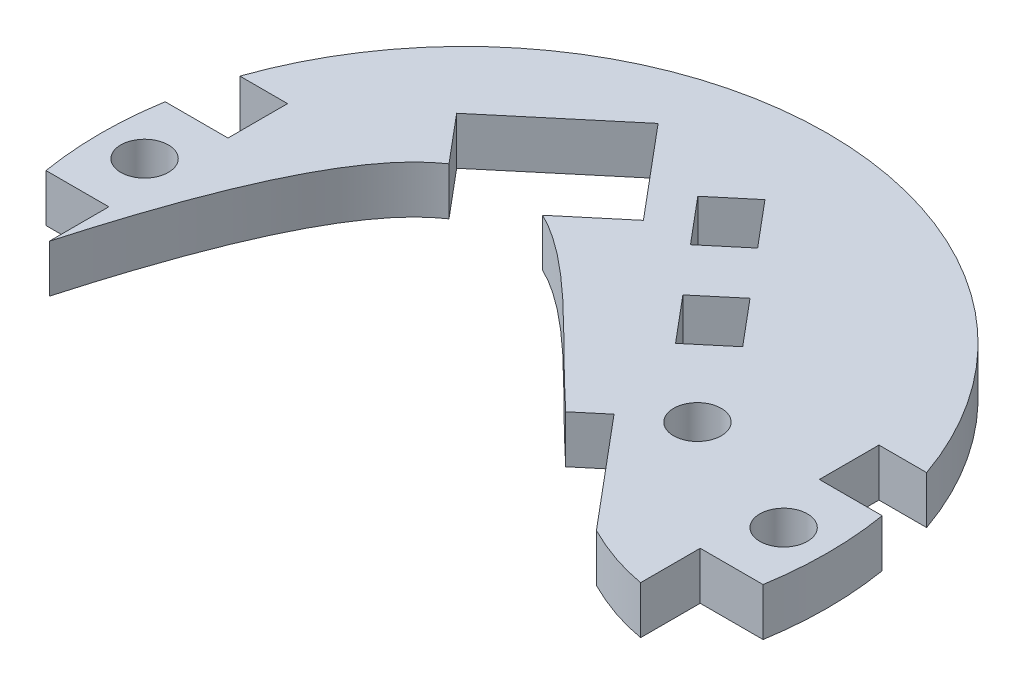
SolidWorks part; units mm, degrees
ref_plane "Alzado" through (0, 0, 0) normal (0, 0, 1) x (1, 0, 0)
ref_plane "Planta" through (0, 0, 0) normal (0, 1, 0) x (1, 0, 0)
ref_plane "Vista lateral" through (0, 0, 0) normal (1, 0, 0) x (0, 0, -1)
sketch "Croquis1" plane through (0, 0, 0) normal (0, 1, 0) x (1, 0, 0)
  circle A0 centre (0, 0) radius 30.5
extrude "Saliente-Extruir1" add sketch "Croquis1" along normal blind 4
sketch "Croquis2" plane through (0, 4, 0) normal (0, 1, 0) x (1, 0, 0)
  circle A0 centre (0, 0) radius 2
extrude "Cortar-Extruir1" cut sketch "Croquis2" against normal blind 4
sketch "Croquis5" plane through (0, 4, 0) normal (0, 1, 0) x (1, 0, 0)
  line L0 (0, 0) -> (0, 10)
  line L1 (28.8141, -5) -> (30.0874, -5)
  line L2 (28.8141, 5) -> (30.0874, 5)
  line L3 (-24.8141, 10) -> (-28.8141, 10)
  line L4 (24.8141, -5) -> (24.8141, -10)
  line L5 (-24.8141, -10) -> (-28.8141, -10)
  line L6 (24.8141, -5) -> (28.8141, -5)
  line L7 (24.8141, 5) -> (24.8141, 10)
  line L8 (-24.8141, 5) -> (-28.8141, 5)
  line L9 (-24.8141, 5) -> (-24.8141, 10)
  line L10 (-24.8141, -5) -> (-28.8141, -5)
  line L11 (-24.8141, -5) -> (-24.8141, -10)
  line L12 (24.8141, 5) -> (28.8141, 5)
  line L13 (24.8141, -10) -> (28.8141, -10)
  line L14 (24.8141, 10) -> (28.8141, 10)
  line L15 (-28.8141, 5) -> (-30.0874, 5)
  line L16 (-28.8141, -5) -> (-30.0874, -5)
  circle A1 centre (0, 0) radius 30.5 construction
  arc A2 (-28.8141, 10) -> (-30.0874, 5) centre (0, 0) ccw
  arc A3 (28.8141, 10) -> (28.8141, -10) centre (0, 0) cw
  arc A4 (-30.0874, -5) -> (-28.8141, -10) centre (0, 0) ccw
  arc A5 (30.0874, -5) -> (28.8141, -10) centre (0, 0) cw
  arc A6 (28.8141, 10) -> (30.0874, 5) centre (0, 0) cw
extrude "Cortar-Extruir3" cut sketch "Croquis5" against normal blind 4
sketch "Croquis7" plane through (0, 4, 0) normal (0, 1, 0) x (1, 0, 0)
  line L0 (-8.1011, 29.1011) -> (9.5756, 8.0348)
  line L2 (-8.1011, 29.1011) -> (-27.2522, 13.0314)
  line L3 (27.2522, -13.0314) -> (8.1011, -29.1011)
  line L4 (8.1011, -29.1011) -> (-27.2522, 13.0314)
  line L5 (2.1944, 23.0542) -> (-0.8697, 20.4831)
  line L6 (2.1944, 23.0542) -> (5.4084, 19.224)
  line L7 (5.4084, 19.224) -> (2.3442, 16.6528)
  line L8 (2.3442, 16.6528) -> (-0.8697, 20.4831)
  line L9 (-24.8141, -10) -> (-28.8141, -10)
  line L10 (24.8141, -10) -> (28.8141, -10)
  line L11 (9.5756, 8.0348) -> (18.4139, -2.4983)
  line L12 (18.4139, -2.4983) -> (27.2522, -13.0314)
  line L13 (11.4555, 1.1272) -> (19.169, -8.0653)
  line L14 (19.169, -8.0653) -> (9.9765, -15.7788)
  line L15 (9.9765, -15.7788) -> (2.263, -6.5863)
  line L16 (11.4555, 1.1272) -> (2.263, -6.5863)
  line L17 (-1.4002, 16.4481) -> (-7.8281, 24.1085)
  line L18 (-1.4002, 16.4481) -> (-10.5927, 8.7346)
  line L19 (-10.5927, 8.7346) -> (-17.0206, 16.3951)
  line L20 (-7.8281, 24.1085) -> (-17.0206, 16.3951)
  arc A1 (-28.8141, -10) -> (28.8141, -10) centre (0, 0) ccw
  circle A2 centre (15.5268, 4.0539) radius 2
  spline S0 degree 3 poles (24.8141, -10) (2.6081, -6.0995) (-10.3265, 41.1093) (-24.8141, -10) knots 0 0 0 0 1 1 1 1
  point P7 (-9.5756, -8.0348)
extrude "Cortar-Extruir5" cut sketch "Croquis7" against normal blind 4
sketch "Croquis9" plane through (0, 4, 0) normal (0, 1, 0) x (1, 0, 0)
  line L0 (-8.3073, 29.3469) -> (22.8679, -7.8063)
  line L2 (8.7375, 15.2565) -> (11.9514, 11.4263)
  line L3 (-8.3073, 29.3469) -> (-21.7131, 18.0981)
  line L4 (-21.7131, 18.0981) -> (9.4621, -19.0551)
  line L5 (9.4621, -19.0551) -> (22.8679, -7.8063)
  line L6 (11.9514, 11.4263) -> (8.8872, 8.8552)
  line L7 (8.7375, 15.2565) -> (5.6733, 12.6854)
  arc A1 (28.8141, 10) -> (-28.8141, 10) centre (0, 0) ccw construction
extrude "Cortar-Extruir6" cut sketch "Croquis9" against normal blind 10 contours L2 L7 L0 L6
sketch "Croquis10" plane through (0, 4, 0) normal (0, 1, 0) x (1, 0, 0)
  circle A0 centre (-26.8141, 0) radius 2
  circle A1 centre (26.8141, 0) radius 2
extrude "Cortar-Extruir7" cut sketch "Croquis10" against normal blind 4
